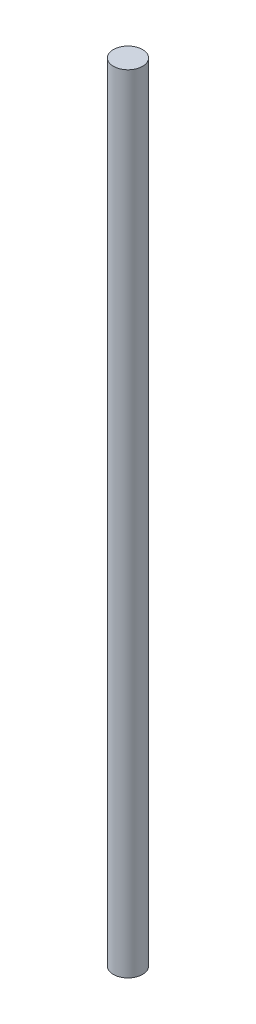
SolidWorks part; units mm, degrees
ref_plane "Front Plane" through (0, 0, 0) normal (0, 0, 1) x (1, 0, 0)
ref_plane "Top Plane" through (0, 0, 0) normal (0, 1, 0) x (1, 0, 0)
ref_plane "Right Plane" through (0, 0, 0) normal (1, 0, 0) x (0, 0, -1)
sketch "Sketch1" plane through (0, 0, 0) normal (0, 1, 0) x (1, 0, 0)
  circle A0 centre (1.3284, 0) radius 5
extrude "Boss-Extrude1" add sketch "Sketch1" along normal blind 270 contours A0
